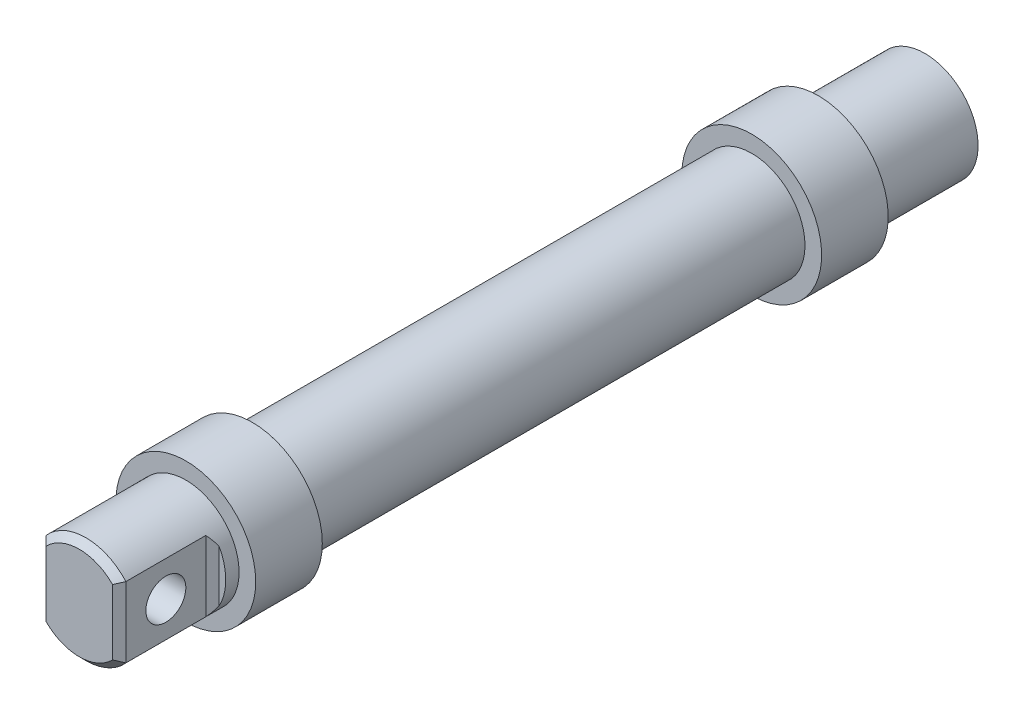
SolidWorks part; units mm, degrees
ref_plane "Front" through (0, 0, 0) normal (0, 0, 1) x (1, 0, 0)
ref_plane "Top" through (0, 0, 0) normal (0, 1, 0) x (1, 0, 0)
ref_plane "Right" through (0, 0, 0) normal (1, 0, 0) x (0, 0, -1)
sketch "Esquisse1" plane through (0, 0, 0) normal (0, 0, 1) x (1, 0, 0)
  circle A0 centre (0, 0) radius 10.5
  dimension "D1" = 21
extrude "Boss.-Extru.1" add sketch "Esquisse1" along normal blind 10
sketch "Esquisse2" plane through (0, 0, 10) normal (0, 0, 1) x (1, 0, 0)
  circle A0 centre (0, 0) radius 8
  dimension "D1" = 16
extrude "Boss.-Extru.2" add sketch "Esquisse2" along normal blind 16
sketch "Esquisse3" plane through (0, 0, 26) normal (0, 0, 1) x (1, 0, 0)
  line L0 (0, 8) -> (0, -8) construction
  line L1 (0, 0) -> (-8, 0) construction
  line L2 (-8, -8) -> (-8, 8)
  line L3 (-8, 8) -> (-6, 8)
  line L4 (-6, 8) -> (-6, -8)
  line L5 (-8, -8) -> (-6, -8)
  line L6 (8, -8) -> (6, -8)
  line L7 (6, 8) -> (6, -8)
  line L8 (8, 8) -> (6, 8)
  line L9 (8, -8) -> (8, 8)
  circle A0 centre (0, 0) radius 8 construction
  circle A1 centre (0, 0) radius 8 construction
  point P10 (-3.2002, 0)
  point P15 (-6, 0)
  point P20 (6, 0)
  dimension "D1" = 12
  dimension "D2" = 8
extrude "Enlèv. mat.-Extru.1" cut sketch "Esquisse3" against normal blind 14
chamfer "Chanfrein1" distance 1 angle 45 6 edges at (0, 8, 26) (0, -8, 26) (-6, 0, 26) (6, 0, 26) (6, 0, 12) (-6, 0, 12)
sketch "Esquisse4" plane through (-6, 0, 0) normal (-1, 0, 0) x (0, 0, 1)
  line L0 (25, 0) -> (19, 0) construction
  line L1 (25, -5.2915) -> (25, 5.2915) construction
  line L2 (10, -10.5) -> (10, 10.5) construction
  circle A0 centre (19, 0) radius 3
  dimension "D1" = 6
  dimension "D2" = 9
extrude "Enlèv. mat.-Extru.2" cut sketch "Esquisse4" against normal through all both and the other way through all
sketch "Esquisse5" plane through (0, 0, 0) normal (0, 0, -1) x (-1, 0, 0)
  circle A0 centre (0, 0) radius 8
  dimension "D1" = 16
extrude "Boss.-Extru.3" add sketch "Esquisse5" along normal blind 85
sketch "Esquisse6" plane through (0, 0, -85) normal (0, 0, -1) x (-1, 0, 0)
  circle A0 centre (0, 0) radius 10.5
  circle A1 centre (0, 0) radius 10.5 construction
extrude "Boss.-Extru.4" add sketch "Esquisse6" against normal blind 10
sketch "Esquisse7" plane through (0, 0, -85) normal (0, 0, -1) x (-1, 0, 0)
  circle A0 centre (0, 0) radius 8
  dimension "D1" = 16
extrude "Boss.-Extru.5" add sketch "Esquisse7" along normal blind 16
sketch "Esquisse8" plane through (0, 0, -101) normal (0, 0, -1) x (-1, 0, 0)
  circle A0 centre (0, 0) radius 3
  dimension "D1" = 6
extrude "Enlèv. mat.-Extru.3" cut sketch "Esquisse8" against normal blind 98
